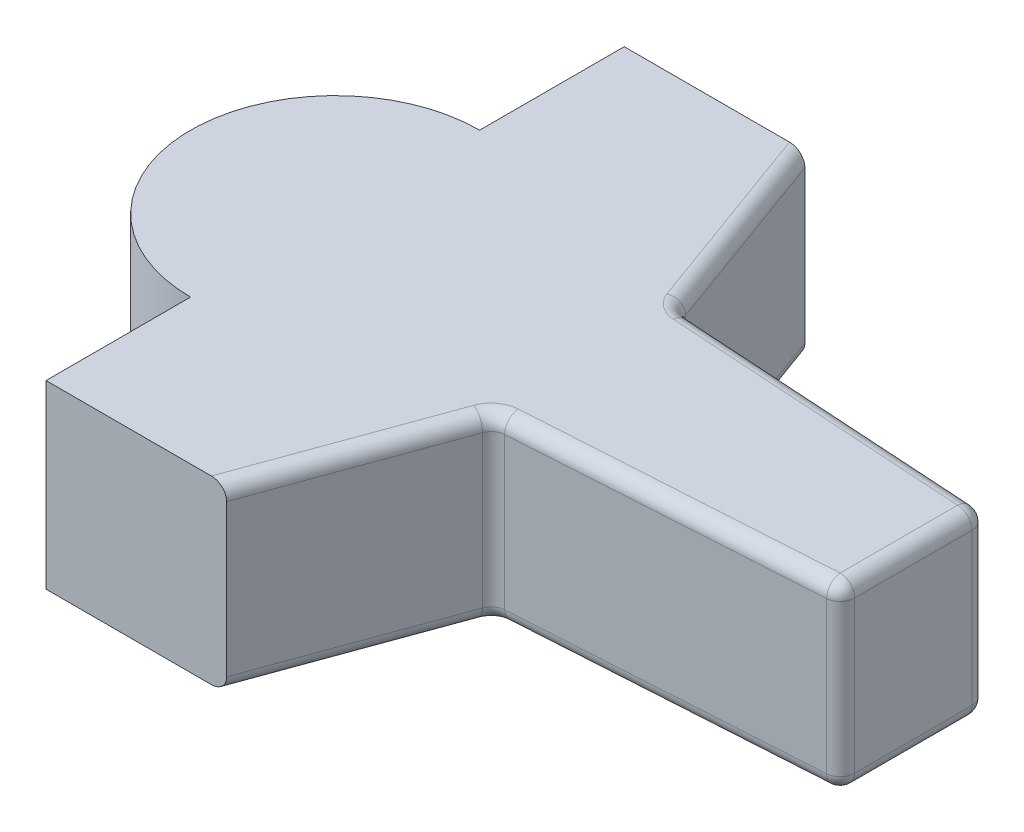
SolidWorks part; units mm, degrees
ref_plane "Front Plane" through (0, 0, 0) normal (1, 0, 0) x (0, 1, 0)
ref_plane "Top Plane" through (0, 0, 0) normal (0, 0, 1) x (0, 1, 0)
ref_plane "Right Plane" through (0, 0, 0) normal (0, 1, 0) x (-1, 0, 0)
sketch "Sketch1" plane through (0, 0, 0) normal (0, 1, 0) x (-1, 0, 0)
  circle A0 centre (0, 0) radius 10
  dimension "D1" = 20
extrude "Boss-Extrude1" add sketch "Sketch1" along normal mid plane 12.5
sketch "Sketch2" plane through (0, 0, 0) normal (0, 1, 0) x (-1, 0, 0)
  line L0 (0, 0) -> (0, 7.5)
  line L1 (0, 7.5) -> (-40, 5)
  line L2 (-40, 5) -> (-40, -5)
  line L3 (-40, -5) -> (0, -7.5)
  line L4 (0, -7.5) -> (0, 0)
  point P3 (-40, 0)
  dimension "D1" = 40
  dimension "D2" = 15
  dimension "D3" = 10
extrude "Boss-Extrude2" add sketch "Sketch2" along normal mid plane 12.5
sketch "Sketch4" plane through (0, 6.25, 0) normal (0, 1, 0) x (1, 0, 0)
  line L0 (19.7794, 0) -> (12.5, -20)
  line L1 (12.5, -20) -> (0, -20)
  line L2 (0, -20) -> (0, 20)
  line L3 (0, 20) -> (12.5, 20)
  line L4 (12.5, 20) -> (19.7794, 0)
  point P5 (0, 0)
  dimension "D1" = 20
  dimension "D2" = 12.5
  dimension "D3" = 40
extrude "Boss-Extrude5" add sketch "Sketch4" against normal through all
fillet "Fillet2" radius 1 4 edges at (40, 0, -5) (40, 0, 5) (17.4465, 0, 6.4096) (17.4465, 0, -6.4096)
fillet "Fillet3" radius 1 18 edges at (14.8613, -6.25, 13.5124) (14.8613, 6.25, 13.5124) (17.5634, -6.25, 6.566) (28.5811, 6.25, 5.7137) (28.5811, -6.25, 5.7137) (39.7288, -6.25, 4.7452) (40, -6.25, 0) (40, 6.25, 0) (39.7288, -6.25, -4.7452) (14.8613, 6.25, -13.5124) (14.8613, -6.25, -13.5124) (17.5634, -6.25, -6.566) (17.5634, 6.25, 6.566) (39.7288, 6.25, 4.7452) (39.7288, 6.25, -4.7452) (17.5634, 6.25, -6.566) (28.5811, -6.25, -5.7137) (28.5811, 6.25, -5.7137)
